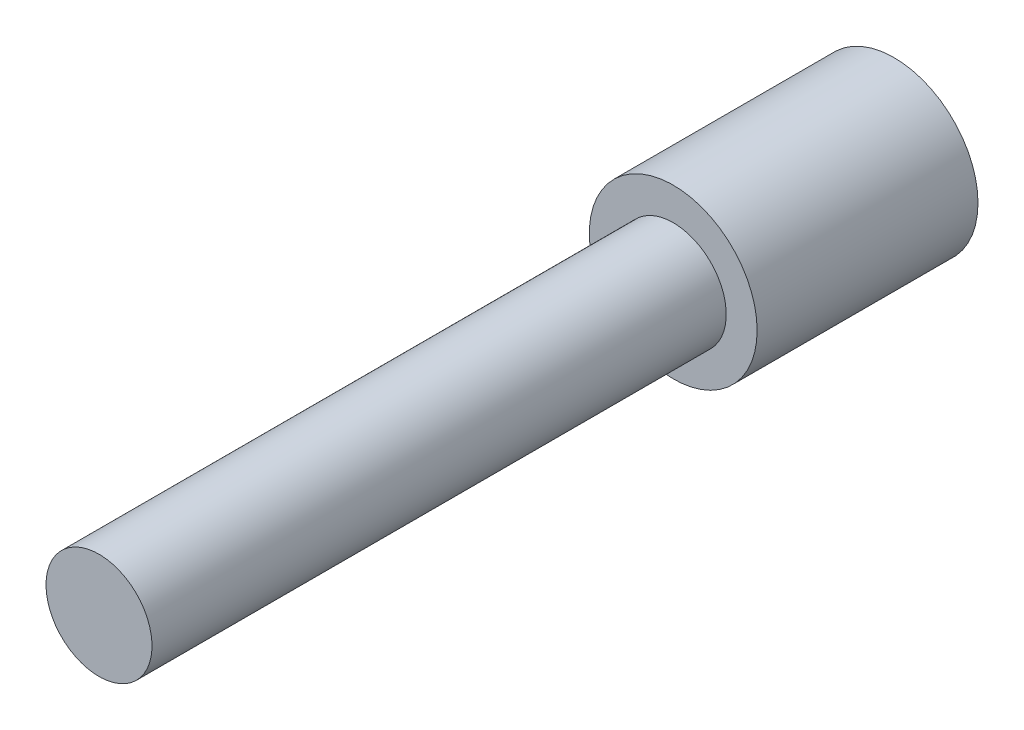
SolidWorks part; units mm, degrees
ref_plane "Front Plane" through (0, 0, 0) normal (0, 0, 1) x (1, 0, 0)
ref_plane "Top Plane" through (0, 0, 0) normal (0, 1, 0) x (1, 0, 0)
ref_plane "Right Plane" through (0, 0, 0) normal (1, 0, 0) x (0, 0, -1)
sketch "Sketch1" plane through (0, 0, 0) normal (0, 0, 1) x (1, 0, 0)
  circle A0 centre (0, 0) radius 6
  dimension "D1" = 12
extrude "Boss-Extrude1" add sketch "Sketch1" along normal blind 90
sketch "Sketch2" plane through (0, 0, 0) normal (1, 0, 0) x (0, 0, -1)
  line L0 (-35.2008, 0.1817) -> (15.248, 0.1817) construction
  line L1 (0, -6) -> (0, 6) construction
  line L2 (-25, 9.6817) -> (0, 9.6817)
  line L3 (-25, 9.6817) -> (-25, 6)
  line L4 (-25, 6) -> (0, 6)
  line L5 (0, 9.6817) -> (0, 6)
  line L6 (0, 6) -> (-90, 6) construction
  dimension "D1" = 25
  dimension "D2" = 19
revolve "Revolve1" add sketch "Sketch2" angle 360 about L0
sketch "Sketch3" plane through (0, 0, 0) normal (0, 0, -1) x (-1, 0, 0)
  circle A0 centre (0, 0) radius 7.5
  dimension "D1" = 15
extrude "Cut-Extrude1" cut sketch "Sketch3" against normal blind 20
